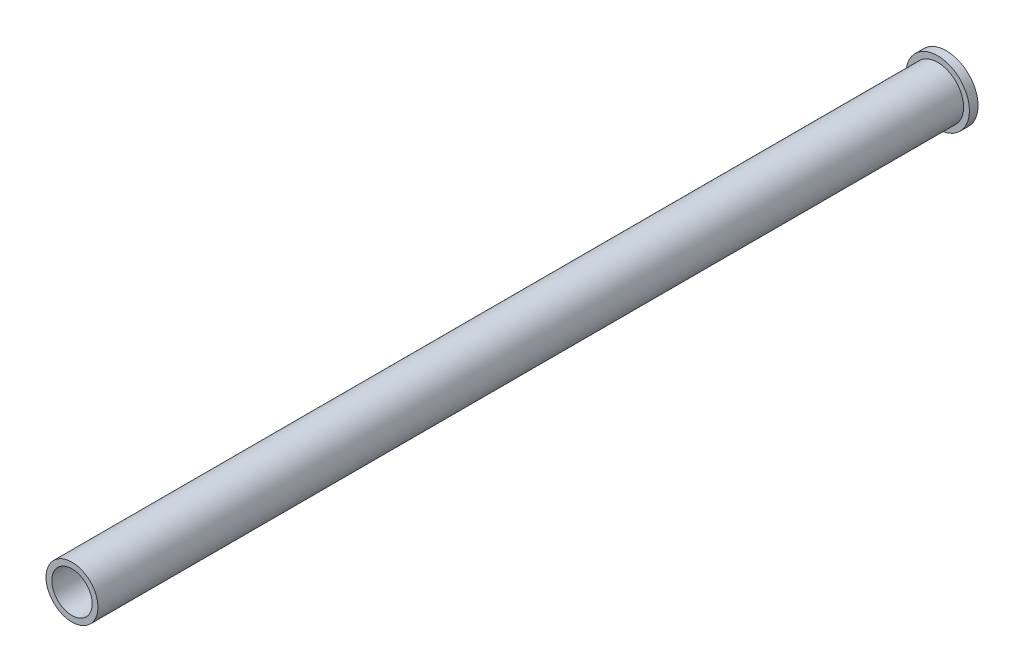
SolidWorks part; units mm, degrees
ref_plane "Front Plane" through (0, 0, 0) normal (0, 0, 1) x (1, 0, 0)
ref_plane "Top Plane" through (0, 0, 0) normal (0, 1, 0) x (1, 0, 0)
ref_plane "Right Plane" through (0, 0, 0) normal (1, 0, 0) x (0, 0, -1)
sketch "Sketch1" plane through (0, 0, 0) normal (0, 0, 1) x (1, 0, 0)
  circle A0 centre (-8.4544, 1.6837) radius 2.794
  dimension "D1" = 5.588
extrude "Boss-Extrude1" add sketch "Sketch1" along normal blind 0.762
sketch "Sketch2" plane through (0, 0, 0.762) normal (0, 0, 1) x (1, 0, 0)
  circle A0 centre (-8.4544, 1.6837) radius 2.286
  dimension "D1" = 4.572
extrude "Boss-Extrude2" add sketch "Sketch2" along normal blind 76.2
sketch "Sketch3" plane through (0, 0, 76.962) normal (0, 0, 1) x (1, 0, 0)
  circle A0 centre (-8.4544, 1.6837) radius 1.778
  dimension "D1" = 3.556
extrude "Cut-Extrude1" cut sketch "Sketch3" against normal blind 12.7
